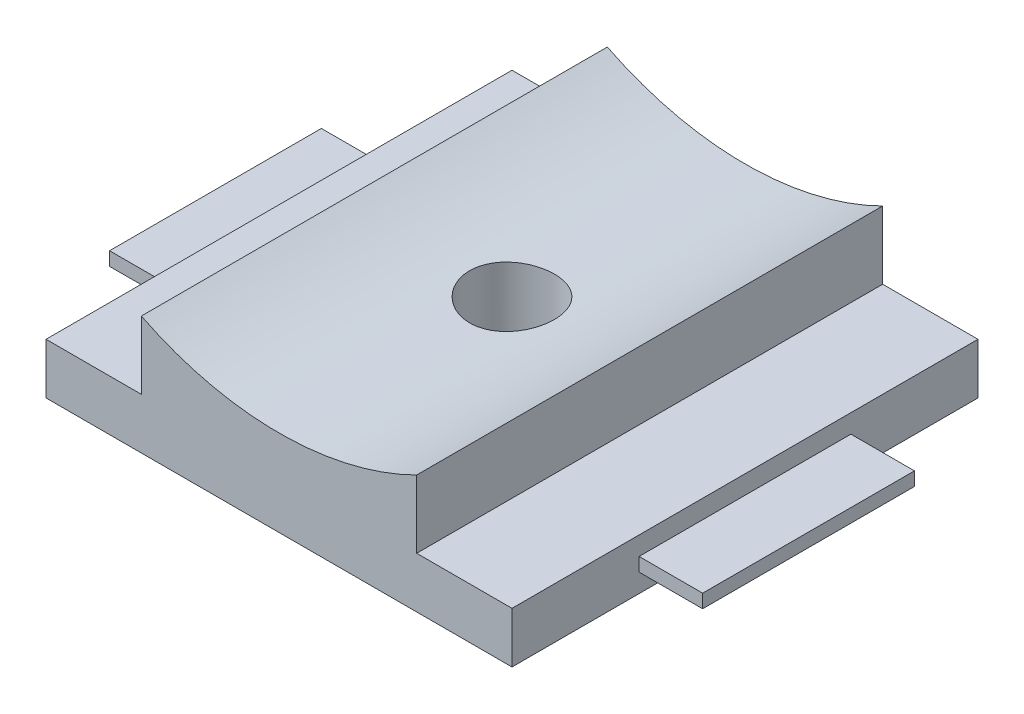
SolidWorks part; units mm, degrees
ref_plane "Front Plane" through (0, 0, 0) normal (0, 0, 1) x (1, 0, 0)
ref_plane "Top Plane" through (0, 0, 0) normal (0, 1, 0) x (1, 0, 0)
ref_plane "Right Plane" through (0, 0, 0) normal (1, 0, 0) x (0, 0, -1)
sketch "Sketch1" plane through (0, 0, 0) normal (0, 0, 1) x (1, 0, 0)
  line L0 (-19.3501, -11.5614) -> (-19.3501, -4.4494) construction
  line L1 (-25.0651, -11.5614) -> (2.8749, -11.5614)
  line L2 (-25.0651, -11.5614) -> (-25.0651, -8.5134)
  line L3 (-25.0651, -8.5134) -> (-19.3501, -8.5134)
  line L4 (2.8749, -11.5614) -> (2.8749, -8.5134)
  line L5 (-25.0651, -11.5614) -> (2.8749, -8.5134) construction
  line L6 (-25.0651, -8.5134) -> (2.8749, -11.5614) construction
  line L7 (-2.8401, -11.5614) -> (-2.8401, -4.4494) construction
  line L8 (-11.0951, -10.0374) -> (-11.0951, -11.5614) construction
  line L9 (-2.8401, -8.5134) -> (2.8749, -8.5134)
  line L11 (-2.8401, -4.4494) -> (-2.8401, -8.5134)
  line L12 (-19.3501, -4.4494) -> (-19.3501, -8.5134)
  arc A0 (-19.3501, -4.4494) -> (-2.8401, -4.4494) centre (-11.0951, 12.0849) ccw
  point P0 (-11.0951, -10.0374)
  dimension "D1" = 27.94
  dimension "D2" = 3.048
  dimension "D3" = 8.255
  dimension "D4" = 8.255
extrude "Boss-Extrude1" add sketch "Sketch1" along normal blind 27.94
sketch "Sketch2" plane through (0, -11.5614, 0) normal (0, -1, 0) x (1, 0, 0)
  line L0 (-25.0651, 27.94) -> (2.8749, 0) construction
  line L1 (-25.0651, 0) -> (2.8749, 27.94) construction
  circle A0 centre (-11.0951, 13.97) radius 2.54
  dimension "D1" = 5.08
extrude "Cut-Extrude1" cut sketch "Sketch2" against normal up to next
sketch "Sketch3" plane through (2.8749, 0, 0) normal (1, 0, 0) x (0, 0, -1)
  line L0 (-27.94, -11.5614) -> (0, -8.5134) construction
  line L2 (-7.62, -10.4438) -> (-20.32, -10.4438)
  line L3 (-7.62, -10.4438) -> (-7.62, -9.631)
  line L4 (-7.62, -9.631) -> (-20.32, -9.631)
  line L5 (-20.32, -10.4438) -> (-20.32, -9.631)
  line L6 (-7.62, -10.4438) -> (-20.32, -9.631) construction
  line L7 (-7.62, -9.631) -> (-20.32, -10.4438) construction
  point P4 (-13.97, -10.0374)
  dimension "D1" = 12.7
  dimension "D2" = 0.8128
extrude "Boss-Extrude2" add sketch "Sketch3" along normal blind 3.81
sketch "Sketch4" plane through (-25.0651, 0, 0) normal (-1, 0, 0) x (0, 0, 1)
  line L0 (27.94, -8.5134) -> (0, -11.5614) construction
  line L2 (7.62, -9.631) -> (20.32, -9.631)
  line L3 (7.62, -9.631) -> (7.62, -10.4438)
  line L4 (7.62, -10.4438) -> (20.32, -10.4438)
  line L5 (20.32, -9.631) -> (20.32, -10.4438)
  line L6 (7.62, -9.631) -> (20.32, -10.4438) construction
  line L7 (7.62, -10.4438) -> (20.32, -9.631) construction
  point P4 (13.97, -10.0374)
  dimension "D1" = 0.8128
  dimension "D2" = 12.7
extrude "Boss-Extrude3" add sketch "Sketch4" along normal blind 3.81
